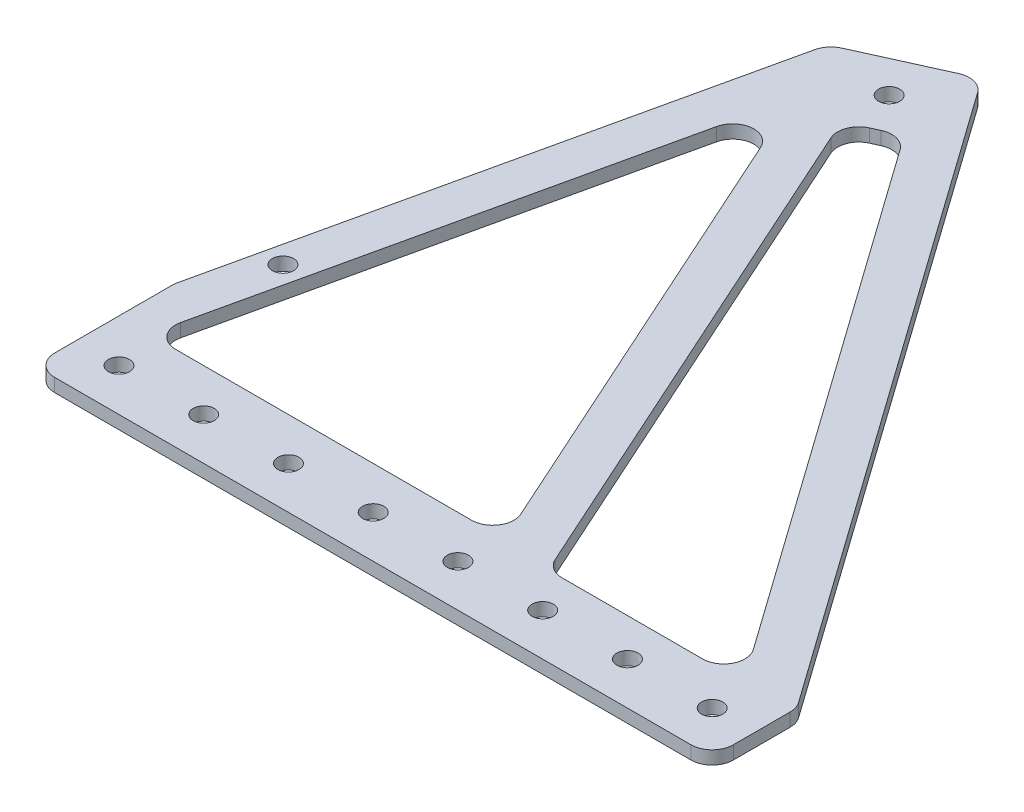
SolidWorks part; units mm, degrees
ref_plane "Front Plane" through (0, 0, 0) normal (0, 0, 1) x (1, 0, 0)
ref_plane "Top Plane" through (0, 0, 0) normal (0, 1, 0) x (1, 0, 0)
ref_plane "Right Plane" through (0, 0, 0) normal (1, 0, 0) x (0, 0, -1)
sketch "Sketch1" plane through (0, 0, 0) normal (0, 1, 0) x (1, 0, 0)
  line L0 (-16, 0) -> (16, 0) construction
  line L1 (-31.2294, 8) -> (-76.046, 107.188)
  line L2 (-24, -8) -> (24, -8)
  line L5 (24, -8) -> (24, 8)
  line L6 (0, 8) -> (0, -8) construction
  line L7 (-24, 0) -> (24, 0) construction
  line L8 (-81.5242, 119.3123) -> (-61.4758, 128.3709)
  line L9 (-61.4758, 128.3709) -> (24, 8)
  line L10 (-67.5, 116.9134) -> (0, 0) construction
  line L11 (-67.5, 116.9134) -> (-71.5, 123.8416) construction
  line L12 (-63.4802, 109.951) -> (-59.4883, 111.7547)
  line L13 (24, -8) -> (-24, -8) construction
  line L14 (24, -8) -> (24, 8) construction
  line L15 (24, 8) -> (-24, 8) construction
  line L16 (-24, -8) -> (-24, 8) construction
  line L17 (0, 8) -> (0, -8) construction
  line L18 (24, 0) -> (-24, 0) construction
  line L19 (-63.4802, 109.951) -> (-67.662, 108.0615)
  line L20 (-67.662, 108.0615) -> (-22.058, 7.1309)
  line L21 (-22.058, 7.1309) -> (14.8053, 7.1309)
  line L22 (14.8053, 7.1309) -> (-59.4883, 111.7547)
  line L23 (-81.5242, 119.3123) -> (-104.1269, 18.5896)
  line L24 (-104.1269, -8) -> (-86.0937, -8)
  line L25 (-98.3042, 8) -> (-76.046, 107.188)
  line L26 (-98.3042, 8) -> (-31.2294, 8)
  line L27 (-86.0937, -8) -> (-24, -8)
  line L28 (-104.1269, -8) -> (-104.1269, 18.5896)
  line L29 (-96, 0) -> (-97.0217, 31.9837) construction
  circle A0 centre (-16, 0) radius 2
  circle A1 centre (16, 0) radius 2
  circle A2 centre (0, 0) radius 2
  circle A3 centre (-67.5, 116.9134) radius 2
  circle A4 centre (-32, 0) radius 2
  circle A5 centre (-48, 0) radius 2
  circle A6 centre (-64, 0) radius 2
  circle A7 centre (-80, 0) radius 2
  circle A8 centre (-96, 0) radius 2
  circle A11 centre (-97.0217, 31.9837) radius 2
  point P3 (-71.5, 123.8416)
  point P4 (0, 0)
  point P7 (0, 0)
  point P20 (-63.4802, 109.951)
  point P23 (-3.6263, 7.1309)
  dimension "D2" = 4
  dimension "D15" = 4
  dimension "D12" = 4
  dimension "D1" = 32
  dimension "D3" = 60
  dimension "D4" = 8
  dimension "D5" = 22
  dimension "D6" = 8
  dimension "D7" = 135
  dimension "D8" = 143
  dimension "D9" = 8
  dimension "D10" = 8
  dimension "D13" = 12
  dimension "D14" = 8
  dimension "D16" = 32
  dimension "D11" = 6
extrude "Boss-Extrude1" add sketch "Sketch1" along normal blind 2.5
fillet "Fillet2" radius 4 13 edges at (-67.662, 1.25, -108.0615) (-59.4883, 1.25, -111.7547) (-22.058, 1.25, -7.1309) (24, 1.25, 8) (24, 1.25, -8) (14.8053, 1.25, -7.1309) (-61.4758, 1.25, -128.3709) (-76.046, 1.25, -107.188) (-81.5242, 1.25, -119.3123) (-31.2294, 1.25, -8) (-98.3042, 1.25, -8) (-104.1269, 1.25, 8) (-104.1269, 1.25, -18.5896)
